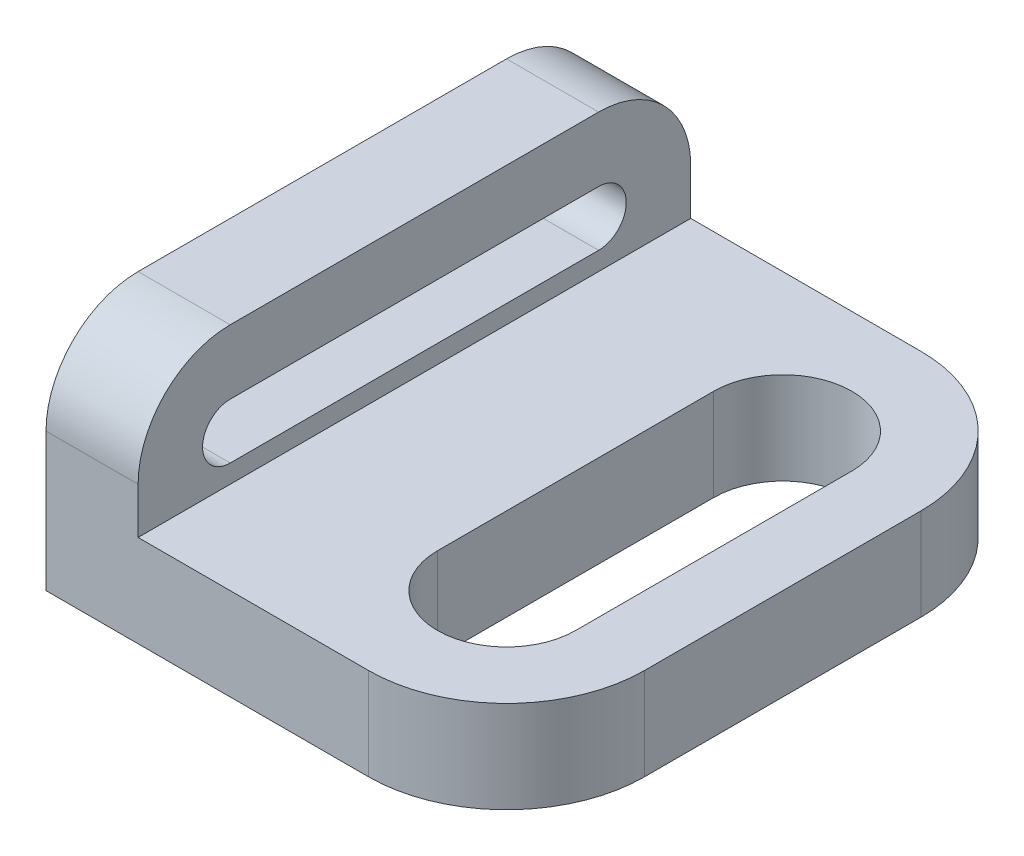
SolidWorks part; units mm, degrees
material "Ductile Iron"
ref_plane "Front Plane" through (0, 0, 0) normal (0, 0, 1) x (1, 0, 0)
ref_plane "Top Plane" through (0, 0, 0) normal (0, 1, 0) x (1, 0, 0)
ref_plane "Right Plane" through (0, 0, 0) normal (1, 0, 0) x (0, 0, -1)
sketch "Sketch1" plane through (0, 0, 0) normal (0, 1, 0) x (1, 0, 0)
  line L0 (0, 75) -> (0, -75) construction
  line L1 (-60, 0) -> (60, 0) construction
  line L2 (20, 71.0168) -> (20, -71.0168) construction
  line L3 (-50, 60) -> (20, 60)
  line L4 (-50, 60) -> (-50, -60)
  line L5 (-50, -60) -> (20, -60)
  line L6 (50, 30) -> (50, -30)
  line L7 (-50, 60) -> (50, -60) construction
  line L8 (-50, -60) -> (50, 60) construction
  line L9 (-18.2943, -30) -> (58.2943, -30) construction
  line L10 (-21.7574, 30) -> (61.7574, 30) construction
  line L11 (35, -30) -> (35, 30)
  line L12 (5, 30) -> (5, -30)
  arc A0 (20, -60) -> (50, -30) centre (20, -30) ccw
  arc A1 (20, 60) -> (50, 30) centre (20, 30) cw
  arc A2 (35, 30) -> (5, 30) centre (20, 30) ccw
  arc A3 (35, -30) -> (5, -30) centre (20, -30) cw
  arc A4 (13.6682, 16.4019) -> (20, 15) centre (20, 30) ccw
  point P0 (0, 0)
  point P4 (0, 0)
  point P8 (0, 0)
  point P21 (20, 0)
  point P23 (20, -30)
  point P24 (-72.9775, -91.1952)
  point P27 (20, 30)
  dimension "D5" = 30
  dimension "D6" = 30
  dimension "D7" = 15
  dimension "D1" = 150
  dimension "D2" = 120
  dimension "D3" = 100
  dimension "D4" = 120
extrude "Boss-Extrude1" add sketch "Sketch1" along normal blind 20 contours A1 L3 L4 L5 A0 L6 L11 A3 L12 A2
ref_plane "Plane1" through (-50, 0, 0) normal (-1, 0, 0) x (0, 0, 1)
sketch "Sketch3" plane through (-50, 0, 0) normal (1, 0, 0) x (0, 0, -1)
  line L0 (0, 0) -> (0, 35) construction
  line L1 (40, 36) -> (-40, 36)
  line L2 (40, 50) -> (-40, 50)
  line L3 (60, 30) -> (60, 20)
  line L4 (60, 20) -> (-60, 20)
  line L5 (-60, 30) -> (-60, 20)
  line L6 (60, 50) -> (-60, 20) construction
  line L7 (60, 20) -> (-60, 50) construction
  line L8 (-40, 24) -> (40, 24)
  arc A0 (60, 30) -> (40, 50) centre (40, 30) ccw
  arc A1 (-60, 30) -> (-40, 50) centre (-40, 30) cw
  arc A2 (40, 24) -> (40, 36) centre (40, 30) ccw
  arc A3 (-40, 24) -> (-40, 36) centre (-40, 30) cw
  dimension "D2" = 20
  dimension "D3" = 20
  dimension "D4" = 12
  dimension "D1" = 35
extrude "Boss-Extrude2" add sketch "Sketch3" along normal blind 20
